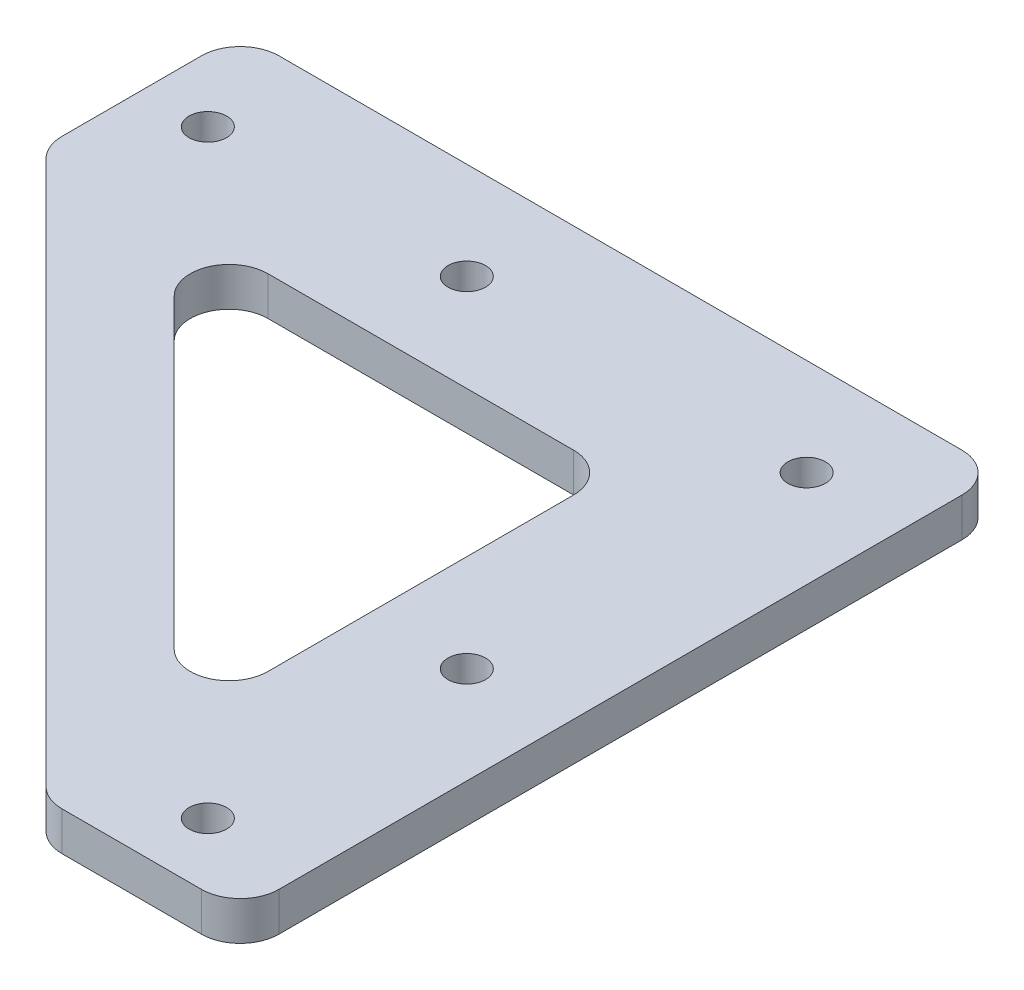
SolidWorks part; units mm, degrees
material "Thornel Mat VMA"
ref_plane "前视基准面" through (0, 0, 0) normal (0, 0, 1) x (1, 0, 0)
ref_plane "上视基准面" through (0, 0, 0) normal (0, 1, 0) x (1, 0, 0)
ref_plane "右视基准面" through (0, 0, 0) normal (1, 0, 0) x (0, 0, -1)
other "Configuration Table"
sketch "草图1" plane through (0, 0, 0) normal (0, 1, 0) x (1, 0, 0)
  line L0 (-51.25, 0) -> (0, 0)
  line L1 (7.5, -15) -> (7.5, -58.75)
  line L2 (7.5, -58.75) -> (-7.5, -58.75)
  line L3 (-7.5, -58.75) -> (-7.5, -15)
  line L4 (-7.5, -15) -> (-51.25, -15)
  line L5 (-51.25, -15) -> (-51.25, 0)
  line L6 (-51.25, -7.5) -> (51.25, -7.5) construction
  line L7 (0, -58.75) -> (0, 0) construction
  line L8 (7.5, -15) -> (51.25, -15)
  line L9 (51.25, -15) -> (51.25, 0)
  line L10 (0, 0) -> (51.25, 0)
  circle A0 centre (0, -7.5) radius 1.45
  circle A1 centre (0, -33.75) radius 1.45
  circle A2 centre (0, -53.75) radius 1.45
  circle A3 centre (-26.25, -7.5) radius 1.45
  circle A4 centre (-46.25, -7.5) radius 1.45
  circle A5 centre (46.25, -7.5) radius 1.45
  circle A6 centre (26.25, -7.5) radius 1.45
  dimension "D3" = 2.9
  dimension "D4" = 2.9
  dimension "D5" = 2.9
  dimension "D9" = 2.9
  dimension "D10" = 2.9
  dimension "D11" = 26.25
  dimension "D12" = 20
  dimension "D13" = 5
  dimension "D1" = 15
  dimension "D2" = 15
  dimension "D6" = 26.25
  dimension "D7" = 20
  dimension "D8" = 5
extrude "凸台-拉伸1" add sketch "草图1" along normal blind 3
sketch "草图2" plane through (0, 3, 0) normal (0, 1, 0) x (1, 0, 0)
  line L0 (-51.25, -15) -> (-7.5, -58.75)
  line L1 (-7.5, -58.75) -> (-7.5, -48.8505)
  line L2 (-7.5, -15) -> (-7.5, -58.75) construction
  line L3 (-7.5, -48.8505) -> (-41.3505, -15)
  line L4 (-51.25, -15) -> (-7.5, -15) construction
  line L5 (-41.3505, -15) -> (-51.25, -15)
  line L6 (0, 0) -> (0, -58.75) construction
  line L7 (-7.5, -58.75) -> (7.5, -58.75) construction
  line L8 (41.3505, -15) -> (51.25, -15)
  line L9 (7.5, -48.8505) -> (41.3505, -15)
  line L10 (7.5, -58.75) -> (7.5, -48.8505)
  line L11 (51.25, -15) -> (7.5, -58.75)
  dimension "D1" = 7
extrude "凸台-拉伸2" add sketch "草图2" against normal up to surface (3 mm away) up to face at (46.25, 0, 6.05)
sketch "草图4" plane through (0, 3, 0) normal (0, 1, 0) x (1, 0, 0)
  line L0 (7.5, -58.75) -> (7.5, 0)
  line L1 (51.25, 0) -> (-51.25, 0) construction
  line L2 (7.5, 0) -> (51.25, 0)
  line L3 (51.25, 0) -> (51.25, -58.75)
  line L4 (51.25, -58.75) -> (7.5, -58.75)
  line L5 (51.25, -15) -> (51.25, 0) construction
extrude "切除-拉伸2" cut sketch "草图4" against normal through all
fillet "圆角1" radius 3 8 edges at (-7.5, 1.5, 15) (-7.5, 1.5, 48.8505) (-41.3505, 1.5, 15) (-51.25, 1.5, 15) (-7.5, 1.5, 58.75) (7.5, 1.5, 58.75) (7.5, 1.5, 0) (-51.25, 1.5, 0)
